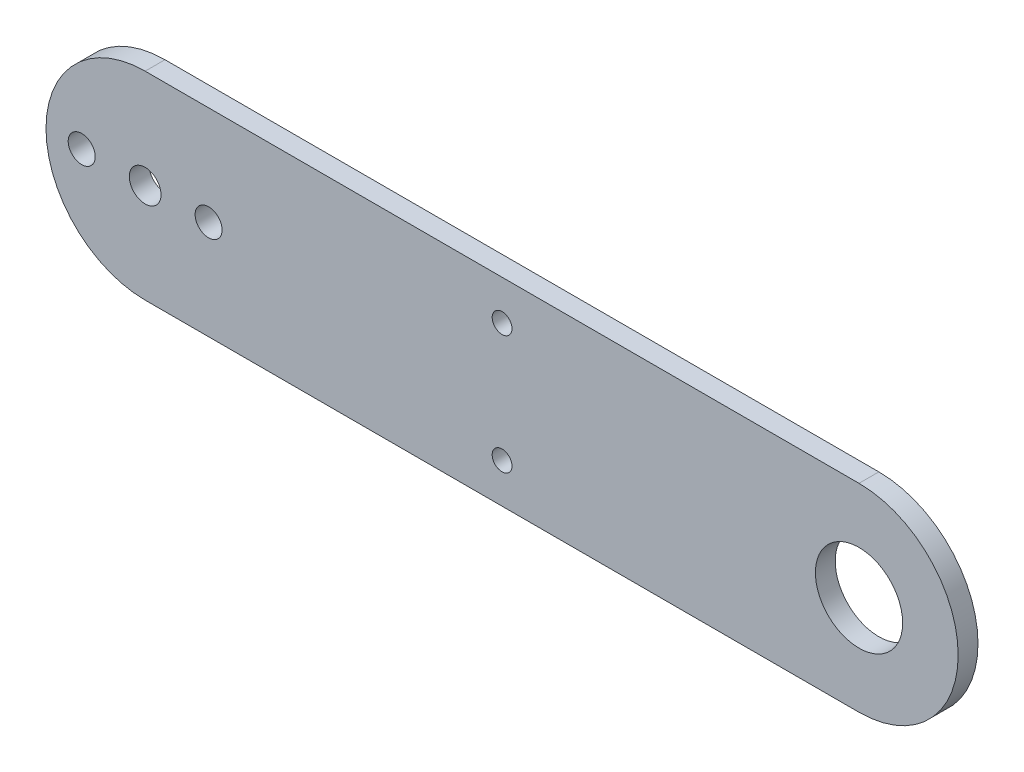
SolidWorks part; units mm, degrees
material "PPE"
ref_plane "Front Plane" through (0, 0, 0) normal (0, 0, 1) x (1, 0, 0)
ref_plane "Top Plane" through (0, 0, 0) normal (0, 1, 0) x (1, 0, 0)
ref_plane "Right Plane" through (0, 0, 0) normal (1, 0, 0) x (0, 0, -1)
sketch "Sketch1" plane through (0, 0, 0) normal (0, 0, 1) x (1, 0, 0)
  line L0 (0, 0) -> (180, 0) construction
  line L1 (0, 25) -> (180, 25)
  line L2 (0, -25) -> (180, -25)
  arc A0 (0, 25) -> (0, -25) centre (0, 0) ccw
  arc A1 (180, -25) -> (180, 25) centre (180, 0) ccw
  circle A2 centre (0, 0) radius 4
  circle A3 centre (-16, 0) radius 3.4
  circle A4 centre (16, 0) radius 3.4
  circle A5 centre (180, 0) radius 11
  point P3 (90, 0)
  dimension "D2" = 25
  dimension "D3" = 6.8
  dimension "D4" = 6.8
  dimension "D5" = 8
  dimension "D6" = 16
  dimension "D7" = 16
  dimension "D8" = 22
  dimension "D1" = 180
extrude "Boss-Extrude3" add sketch "Sketch1" along normal blind 5
sketch "Sketch2" plane through (0, 0, 5) normal (0, 0, 1) x (1, 0, 0)
  line L0 (180, 25) -> (0, 25) construction
  line L1 (0, -25) -> (180, -25) construction
  circle A0 centre (90, 15) radius 2.5
  circle A1 centre (90, -15) radius 2.5
  circle A2 centre (0, 0) radius 4 construction
  dimension "D1" = 5
  dimension "D2" = 5
  dimension "D6" = 90
  dimension "D3" = 10
  dimension "D4" = 10
  dimension "D5" = 90
extrude "Cut-Extrude1" cut sketch "Sketch2" against normal blind 10
